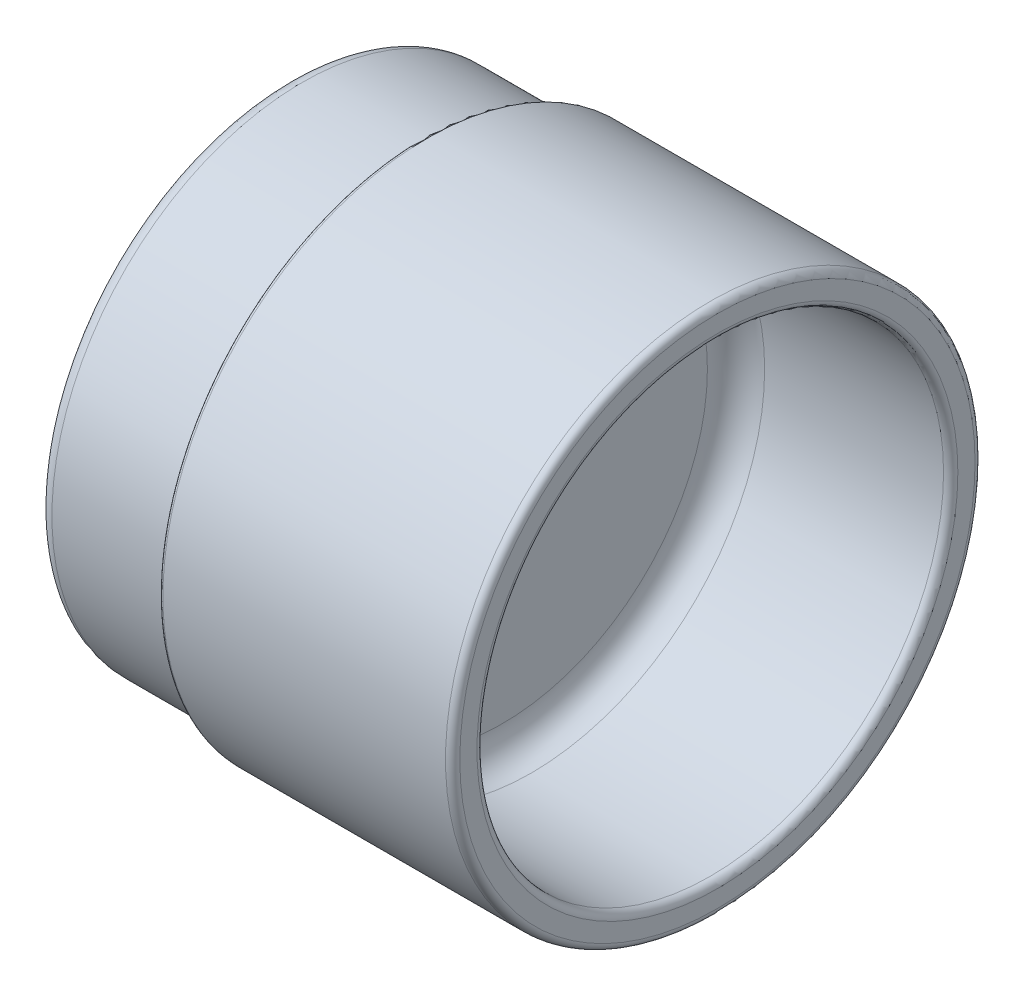
SolidWorks part; units mm, degrees
ref_plane "Front Plane" through (0, 0, 0) normal (0, 0, 1) x (1, 0, 0)
ref_plane "Top Plane" through (0, 0, 0) normal (0, 1, 0) x (1, 0, 0)
ref_plane "Right Plane" through (0, 0, 0) normal (1, 0, 0) x (0, 0, -1)
sketch "Sketch1" plane through (0, 0, 0) normal (0, 1, 0) x (1, 0, 0)
  line L0 (0, 0) -> (0, 33)
  line L1 (2, 35) -> (19, 35)
  line L2 (19, 35) -> (19, 36.5)
  line L3 (19.5, 37) -> (59, 37)
  line L4 (60, 36) -> (60, 33.6)
  line L5 (30, 0) -> (0, 0)
  line L6 (30, 0) -> (-23.9956, 0) construction
  line L7 (59, 32.6) -> (34, 32.6)
  line L8 (30, 28.6) -> (30, 0)
  arc A0 (34, 32.6) -> (30, 28.6) centre (34, 28.6) ccw
  arc A1 (0, 33) -> (2, 35) centre (2, 33) cw
  arc A2 (19, 36.5) -> (19.5, 37) centre (19.5, 36.5) cw
  arc A3 (59, 37) -> (60, 36) centre (59, 36) cw
  arc A4 (59, 32.6) -> (60, 33.6) centre (59, 33.6) ccw
  point P7 (18.0188, 32.6)
  point P13 (30.9935, 35)
  point P14 (12.8672, 35)
  point P15 (19, 39.9825)
  point P18 (0, 35)
  point P21 (19, 37)
  point P24 (60, 37)
  dimension "D4" = 4
  dimension "D8" = 2
  dimension "D9" = 0.5
  dimension "D10" = 1
  dimension "D1" = 70
  dimension "D2" = 60
  dimension "D3" = 65.2
  dimension "D5" = 30
  dimension "D6" = 19
  dimension "D7" = 74
revolve "Revolve1" add sketch "Sketch1" angle 360 about L6
